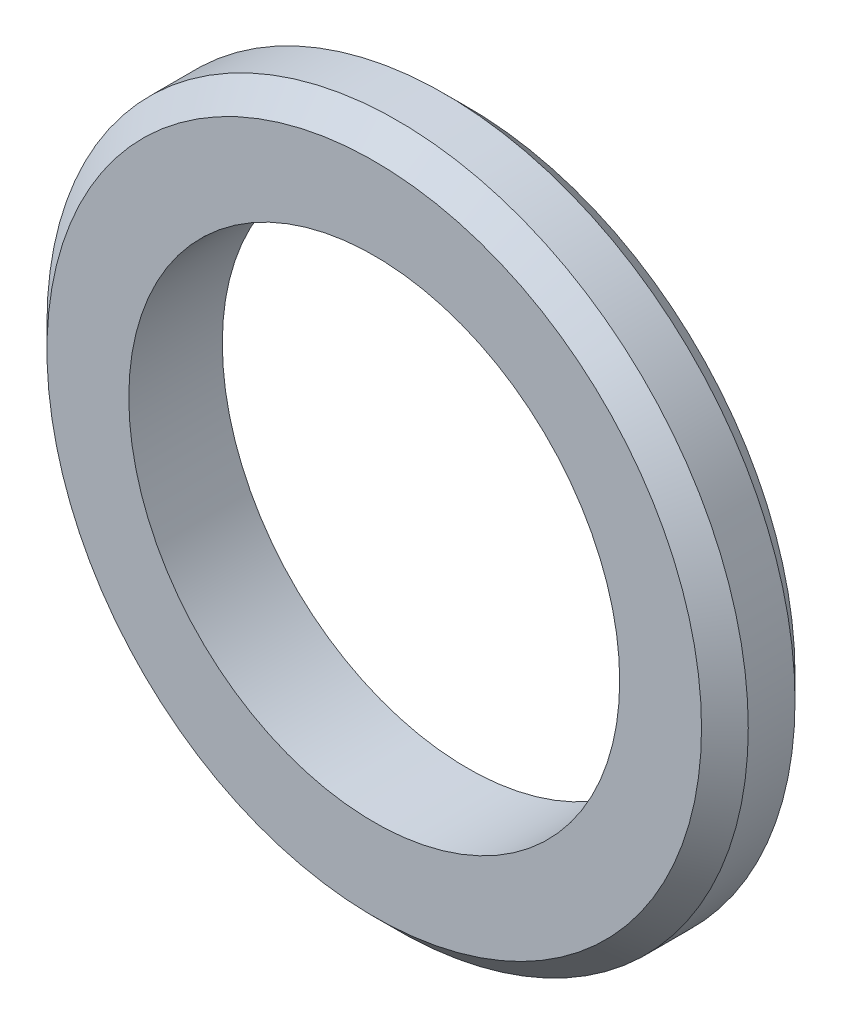
SolidWorks part; units mm, degrees
ref_plane "Front Plane" through (0, 0, 0) normal (0, 0, 1) x (1, 0, 0)
ref_plane "Top Plane" through (0, 0, 0) normal (0, 1, 0) x (1, 0, 0)
ref_plane "Right Plane" through (0, 0, 0) normal (1, 0, 0) x (0, 0, -1)
sketch "Sketch1" plane through (0, 0, 0) normal (0, 0, 1) x (1, 0, 0)
  circle A0 centre (0, 0) radius 7.5
  circle A1 centre (0, 0) radius 5.25
  dimension "D1" = 15
  dimension "D2" = 10.5
extrude "Boss-Extrude1" add sketch "Sketch1" along normal mid plane 2
chamfer "Chamfer1" distance 0.5 angle 45 2 edges at (7.5, 0, -1) (7.5, 0, 1)
